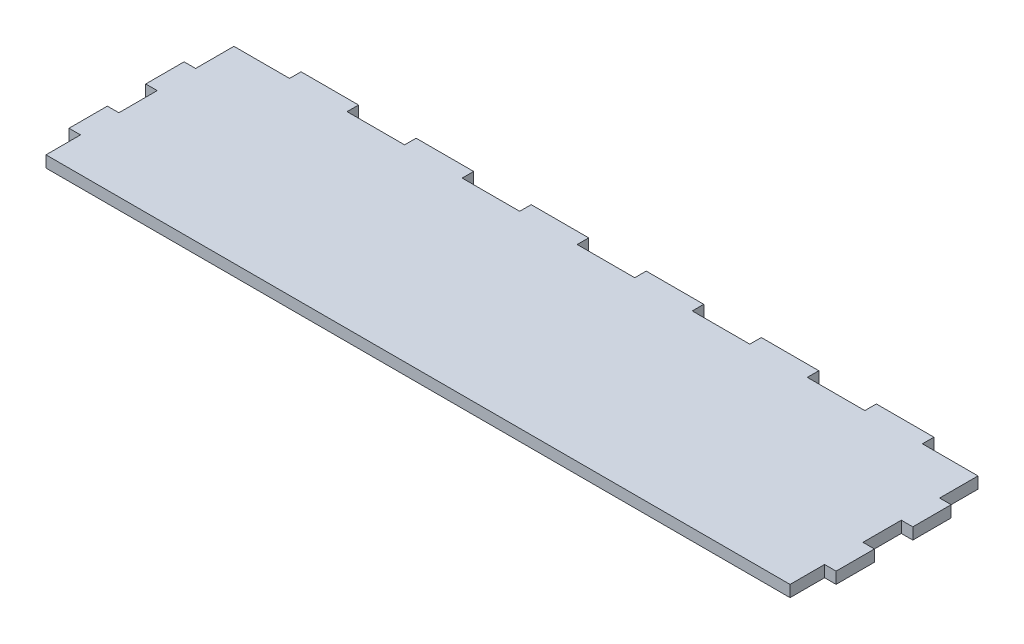
SolidWorks part; units mm, degrees
ref_plane "Front Plane" through (0, 0, 0) normal (0, 0, 1) x (1, 0, 0)
ref_plane "Top Plane" through (0, 0, 0) normal (0, 1, 0) x (1, 0, 0)
ref_plane "Right Plane" through (0, 0, 0) normal (1, 0, 0) x (0, 0, -1)
sketch "Sketch1" plane through (0, 0, 0) normal (0, 1, 0) x (1, 0, 0)
  line L0 (15, 0) -> (0.5, 0)
  line L1 (15, 0) -> (15, 3)
  line L2 (15, 3) -> (30, 3)
  line L3 (30, 3) -> (30, 0)
  line L4 (30, 0) -> (45, 0)
  line L5 (45, 0) -> (45, 3)
  line L6 (45, 3) -> (60, 3)
  line L7 (60, 3) -> (60, 0)
  line L8 (60, 0) -> (75, 0)
  line L9 (75, 0) -> (75, 3)
  line L10 (75, 3) -> (90, 3)
  line L11 (90, 3) -> (90, 0)
  line L12 (90, 0) -> (105, 0)
  line L13 (105, 0) -> (105, 3)
  line L14 (105, 3) -> (120, 3)
  line L15 (120, 3) -> (120, 0)
  line L16 (120, 0) -> (135, 0)
  line L17 (135, 0) -> (135, 3)
  line L18 (135, 3) -> (150, 3)
  line L19 (150, 3) -> (150, 0)
  line L20 (150, 0) -> (165, 0)
  line L21 (165, 0) -> (165, 3)
  line L22 (165, 3) -> (180, 3)
  line L23 (180, 3) -> (180, 0)
  line L24 (180, 0) -> (194.5, 0)
  line L25 (0.5, 0) -> (0.5, -10)
  line L26 (0.5, -10) -> (-2.5, -10)
  line L27 (-2.5, -10) -> (-2.5, -20)
  line L28 (-2.5, -20) -> (0.5, -20)
  line L29 (0.5, -20) -> (0.5, -30)
  line L30 (0.5, -30) -> (-2.5, -30)
  line L31 (-2.5, -30) -> (-2.5, -40)
  line L32 (-2.5, -40) -> (0.5, -40)
  line L33 (0.5, -40) -> (0.5, -49)
  line L34 (0.5, -49) -> (194.5, -49)
  line L35 (97.5, 0) -> (97.5, -49) construction
  line L36 (194.5, -40) -> (194.5, -49)
  line L37 (197.5, -40) -> (194.5, -40)
  line L38 (197.5, -30) -> (197.5, -40)
  line L39 (194.5, -30) -> (197.5, -30)
  line L40 (194.5, -20) -> (194.5, -30)
  line L41 (197.5, -20) -> (194.5, -20)
  line L42 (197.5, -10) -> (197.5, -20)
  line L43 (194.5, -10) -> (197.5, -10)
  line L44 (194.5, 0) -> (194.5, -10)
  dimension "D1" = 6
  dimension "D2" = 15
  dimension "D3" = 3
  dimension "D4" = 3
  dimension "D6" = 14.5
  dimension "D7" = 10
  dimension "D8" = 10
  dimension "D9" = 3
  dimension "D10" = 10
  dimension "D11" = 10
  dimension "D12" = 9
extrude "Boss-Extrude1" add sketch "Sketch1" along normal blind 3
